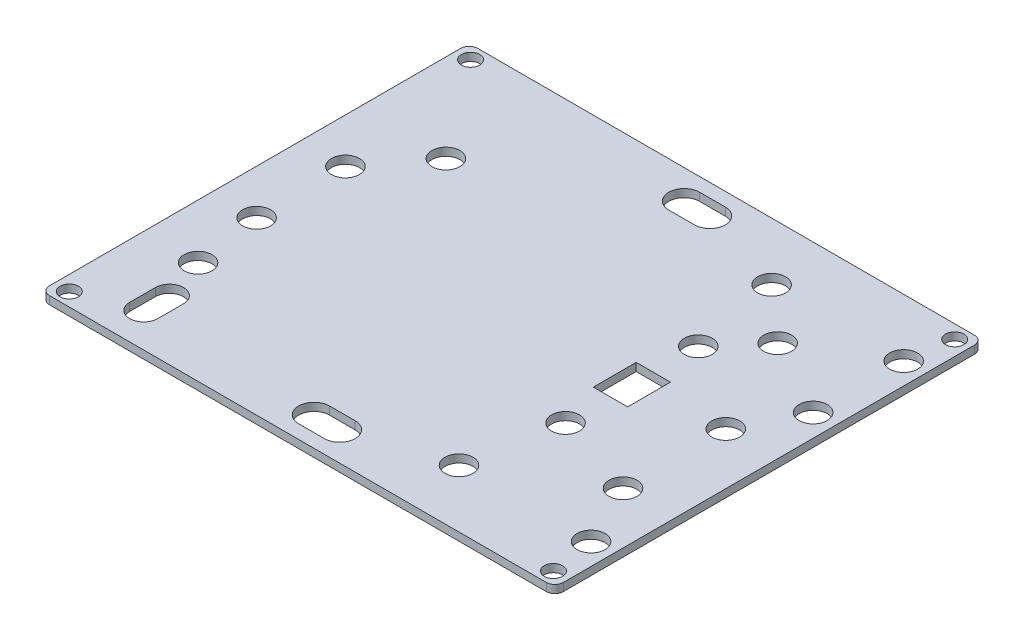
SolidWorks part; units mm, degrees
material "PE High Density Film"
ref_plane "Front Plane" through (0, 0, 0) normal (0, 0, 1) x (1, 0, 0)
ref_plane "Top Plane" through (0, 0, 0) normal (0, 1, 0) x (1, 0, 0)
ref_plane "Right Plane" through (0, 0, 0) normal (1, 0, 0) x (0, 0, -1)
sketch "Sketch1" plane through (0, 0, 0) normal (0, 1, 0) x (1, 0, 0)
  line L1 (-76.2, 63.5) -> (76.2, 63.5)
  line L2 (-76.2, 63.5) -> (-76.2, -63.5)
  line L3 (-76.2, -63.5) -> (76.2, -63.5)
  line L4 (76.2, 63.5) -> (76.2, -63.5)
  line L5 (-76.2, 63.5) -> (76.2, -63.5) construction
  line L6 (-76.2, -63.5) -> (76.2, 63.5) construction
  point P0 (0, 0)
  dimension "D1" = 127
  dimension "D2" = 152.4
extrude "Boss-Extrude1" add sketch "Sketch1" along normal blind 2.3622
fillet "Fillet1" radius 2.54 4 edges at (76.2, 1.1811, 63.5) (76.2, 1.1811, -63.5) (-76.2, 1.1811, -63.5) (-76.2, 1.1811, 63.5)
sketch "Sketch9" plane through (0, 0, 0) normal (0, -1, 0) x (1, 0, 0)
  circle A0 centre (60.8584, 27.94) radius 4.15
  circle A1 centre (60.8584, -2.54) radius 4.15
  dimension "D1" = 8.3
  dimension "D2" = 8.3
extrude "Cut-Extrude8" cut sketch "Sketch9" against normal through all
sketch "Sketch12" plane through (0, 0, 0) normal (0, -1, 0) x (1, 0, 0)
  line L0 (-3.81, 54.8882) -> (3.81, 54.8882) construction
  line L1 (-3.81, 59.4656) -> (3.81, 59.4656)
  line L2 (-3.81, 50.3108) -> (3.81, 50.3108)
  line L3 (76.2, 60.96) -> (76.2, -60.96) construction
  arc A0 (-3.81, 59.4656) -> (-3.81, 50.3108) centre (-3.81, 54.8882) ccw
  arc A1 (3.81, 50.3108) -> (3.81, 59.4656) centre (3.81, 54.8882) ccw
  point P2 (0, 54.8882)
  dimension "D1" = 7.62
  dimension "D2" = 76.2
extrude "Cut-Extrude11" cut sketch "Sketch12" against normal through all
mirror "Mirror3" about plane through (0, 0, 0) normal (0, 0, 1) of "Cut-Extrude11"
sketch "Sketch13" plane through (0, 0, 0) normal (0, -1, 0) x (-1, 0, 0)
  line L0 (55.88, -45.72) -> (55.88, -53.34) construction
  line L1 (60.0529, -45.72) -> (60.0529, -53.34)
  line L2 (51.7071, -45.72) -> (51.7071, -53.34)
  line L3 (73.66, -63.5) -> (-73.66, -63.5) construction
  line L4 (76.2, 61.0698) -> (76.2, -60.8502) construction
  arc A0 (60.0529, -45.72) -> (51.7071, -45.72) centre (55.88, -45.72) ccw
  arc A1 (51.7071, -53.34) -> (60.0529, -53.34) centre (55.88, -53.34) ccw
  point P2 (55.88, -49.53)
  dimension "D1" = 7.62
  dimension "D2" = 10.16
  dimension "D3" = 20.32
extrude "Cut-Extrude12" cut sketch "Sketch13" against normal through all
sketch "Sketch16" plane through (0, 0, 0) normal (0, -1, 0) x (-1, 0, 0)
  circle A0 centre (-69.5999, 19.7043) radius 4.15
  circle A1 centre (-46.5226, 32.2642) radius 4.15
  dimension "D1" = 8.3
extrude "Cut-Extrude14" cut sketch "Sketch16" against normal through all
sketch "Sketch17" plane through (0, 0, 0) normal (0, -1, 0) x (1, 0, 0)
  circle A0 centre (71.7948, 59.5104) radius 2.7305
  dimension "D1" = 5.461
extrude "Cut-Extrude16" cut sketch "Sketch17" against normal through all
mirror "Mirror6" about plane through (0, 0, 0) normal (1, 0, 0) of "Cut-Extrude16"
mirror "Mirror7" about plane through (0, 0, 0) normal (0, 0, 1) of "Mirror6", "Cut-Extrude16"
sketch "Sketch26" plane through (0, 2.3622, 0) normal (0, 1, 0) x (1, 0, 0)
  line L1 (40.64, 6.35) -> (30.48, 6.35)
  line L2 (40.64, 6.35) -> (40.64, -6.35)
  line L3 (40.64, -6.35) -> (30.48, -6.35)
  line L4 (30.48, 6.35) -> (30.48, -6.35)
extrude "Cut-Extrude26" cut sketch "Sketch26" against normal through all
sketch "Sketch27" plane through (0, 0, 0) normal (0, -1, 0) x (1, 0, 0)
  circle A0 centre (-60.0917, 33.02) radius 4.15
  circle A1 centre (-50.0917, -30.48) radius 4.15
  dimension "D1" = 8.3
extrude "Cut-Extrude27" cut sketch "Sketch27" against normal through all
sketch "Sketch29" plane through (0, 2.3622, 0) normal (0, 1, 0) x (1, 0, 0)
  circle A0 centre (35.56, 19.6812) radius 4.15
  circle A1 centre (35.56, -19.6812) radius 4.15
  dimension "D1" = 8.3
extrude "Cut-Extrude28" cut sketch "Sketch29" against normal through all
sketch "Sketch30" plane through (0, 2.3622, 0) normal (0, 1, 0) x (1, 0, 0)
  line L0 (73.66, -63.5) -> (-73.66, -63.5) construction
  line L2 (-73.66, -63.5) -> (73.66, -63.5) construction
  circle A0 centre (69.8033, -46.355) radius 4.15
  circle A1 centre (30.6352, -46.355) radius 4.15
  dimension "D1" = 8.3
  dimension "D2" = 17.145
  dimension "D3" = 17.145
extrude "Cut-Extrude29" cut sketch "Sketch30" against normal through all
mirror "Mirror8" about plane through (0, 0, 0) normal (0, 0, 1) of "Cut-Extrude29"
sketch "Sketch31" plane through (0, 2.3622, 0) normal (0, 1, 0) x (1, 0, 0)
  circle A0 centre (-62.9423, -12.7955) radius 4.15
  circle A1 centre (-62.9423, 13.5496) radius 4.15
  dimension "D1" = 8.3
extrude "Cut-Extrude30" cut sketch "Sketch31" against normal through all
